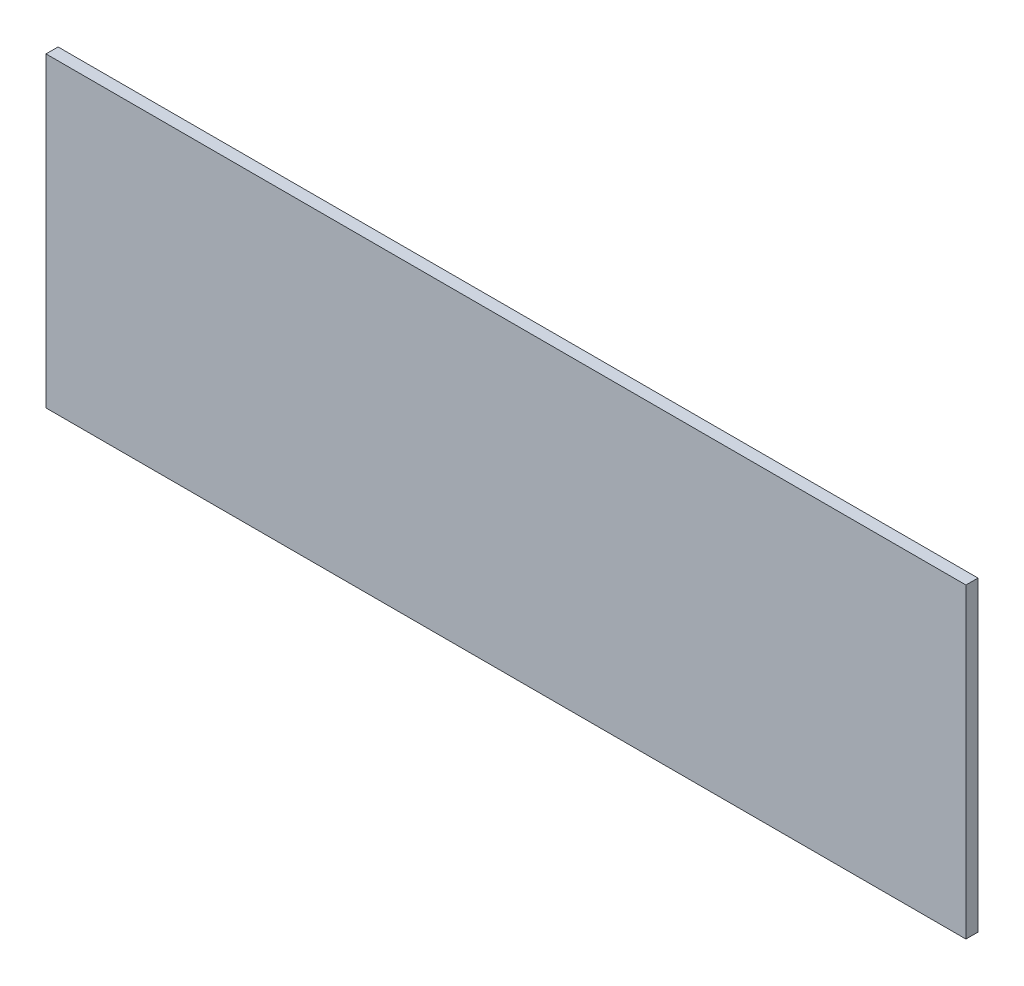
SolidWorks part; units mm, degrees
ref_plane "Front Plane" through (0, 0, 0) normal (0, 0, 1) x (1, 0, 0)
ref_plane "Top Plane" through (0, 0, 0) normal (0, 1, 0) x (1, 0, 0)
ref_plane "Right Plane" through (0, 0, 0) normal (1, 0, 0) x (0, 0, -1)
sketch "Sketch1" plane through (0, 0, 0) normal (0, 0, 1) x (1, 0, 0)
  line L1 (0, 0) -> (76.2, 0)
  line L2 (0, 0) -> (0, 25.4)
  line L3 (0, 25.4) -> (76.2, 25.4)
  line L4 (76.2, 0) -> (76.2, 25.4)
  dimension "D1" = 76.2
  dimension "D2" = 25.4
extrude "Boss-Extrude1" add sketch "Sketch1" along normal blind 1
